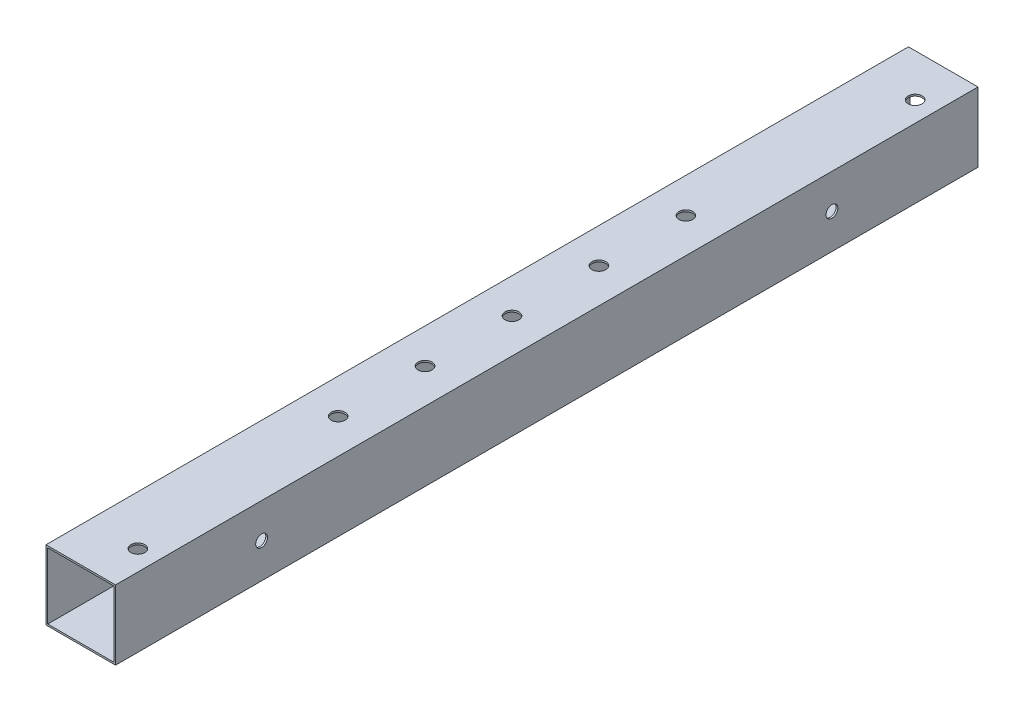
SolidWorks part; units mm, degrees
ref_plane "前视基准面" through (0, 0, 0) normal (0, 0, 1) x (1, 0, 0)
ref_plane "上视基准面" through (0, 0, 0) normal (0, 1, 0) x (1, 0, 0)
ref_plane "右视基准面" through (0, 0, 0) normal (1, 0, 0) x (0, 0, -1)
sketch "草图1" plane through (0, 0, 0) normal (0, 0, 1) x (1, 0, 0)
  line L1 (-10, 10) -> (10, 10)
  line L2 (-10, 10) -> (-10, -10)
  line L3 (-10, -10) -> (10, -10)
  line L4 (10, 10) -> (10, -10)
  line L5 (-10, 10) -> (10, -10) construction
  line L6 (-10, -10) -> (10, 10) construction
  line L7 (9.5, -9.5) -> (-9.5, -9.5)
  line L8 (9.5, -9.5) -> (9.5, 9.5)
  line L9 (9.5, 9.5) -> (-9.5, 9.5)
  line L10 (-9.5, -9.5) -> (-9.5, 9.5)
  line L11 (9.5, -9.5) -> (-9.5, 9.5) construction
  line L12 (9.5, 9.5) -> (-9.5, -9.5) construction
  point P0 (0, 0)
  point P5 (0, 0)
  dimension "D1" = 20
  dimension "D2" = 20
  dimension "D3" = 19
  dimension "D4" = 19
extrude "凸台-拉伸1" add sketch "草图1" against normal blind 248
sketch "草图2" plane through (0, 10, 0) normal (0, 1, 0) x (1, 0, 0)
  line L0 (10, 124) -> (-10, 124) construction
  line L1 (10, 248) -> (10, 0) construction
  line L2 (-10, 248) -> (-10, 0) construction
  circle A1 centre (4.1714, 12.25) radius 2
  circle A2 centre (4.1714, 235.75) radius 2
extrude "切除-拉伸1" cut sketch "草图2" against normal through all
sketch "草图3" plane through (0, 10, 0) normal (0, 1, 0) x (1, 0, 0)
  circle A5 centre (0, 74) radius 2
  circle A6 centre (0, 99) radius 2
  circle A7 centre (0, 124) radius 2
  circle A8 centre (0, 149) radius 2
  circle A9 centre (0, 174) radius 2
extrude "切除-拉伸2" cut sketch "草图3" against normal through all
sketch "草图4" plane through (10, 0, 0) normal (1, 0, 0) x (0, 0, -1)
  circle A1 centre (42, 0) radius 1.7
  circle A3 centre (206, 0) radius 1.7
extrude "切除-拉伸3" cut sketch "草图4" against normal through all
